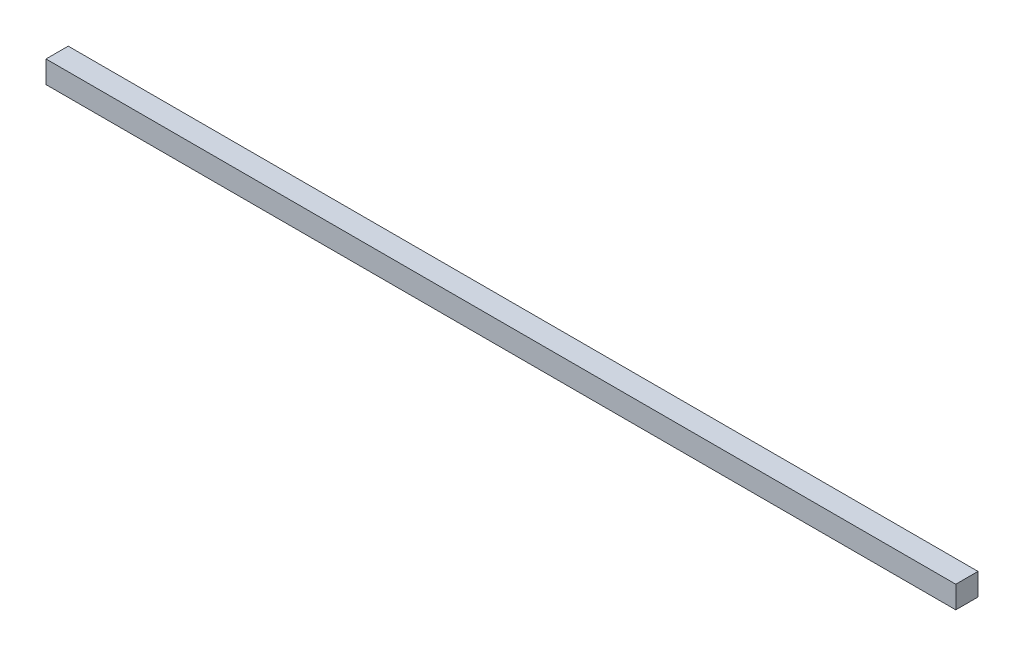
SolidWorks part; units mm, degrees
ref_plane "Front Plane" through (0, 0, 0) normal (0, 0, 1) x (1, 0, 0)
ref_plane "Top Plane" through (0, 0, 0) normal (0, 1, 0) x (1, 0, 0)
ref_plane "Right Plane" through (0, 0, 0) normal (1, 0, 0) x (0, 0, -1)
sketch "Sketch1" plane through (0, 0, 0) normal (1, 0, 0) x (0, 0, -1)
  line L1 (-1.5875, -1.5875) -> (1.5875, -1.5875) construction
  line L2 (-1.5875, -1.5875) -> (-1.5875, 1.5875) construction
  line L3 (-1.5875, 1.5875) -> (1.5875, 1.5875) construction
  line L4 (1.5875, -1.5875) -> (1.5875, 1.5875) construction
  line L5 (-1.5875, -1.5875) -> (1.5875, 1.5875) construction
  line L6 (-1.5875, 1.5875) -> (1.5875, -1.5875) construction
  point P0 (0, 0)
  dimension "Width" = 3.175
  dimension "Thickness" = 3.175
sketch "Sketch2" plane through (0, 0, 0) normal (0, 0, 1) x (1, 0, 0)
  line L0 (-65, 0) -> (65, 0) construction
  point P4 (0, 0)
  dimension "Length" = 130
sketch "Sketch3" plane through (0, 0, 0) normal (1, 0, 0) x (0, 0, -1)
  line L0 (1.5875, -1.5875) -> (1.5875, 1.5875) construction
  line L1 (-1.5875, -1.5875) -> (1.5875, -1.5875) construction
  line L2 (-1.5875, -1.5875) -> (-1.5875, 1.5875) construction
  line L3 (-1.5875, 1.5875) -> (1.5875, 1.5875) construction
  line L4 (1.5875, -1.5875) -> (1.5875, 1.5875)
  line L5 (-1.5875, -1.5875) -> (1.5875, -1.5875)
  line L6 (-1.5875, -1.5875) -> (-1.5875, 1.5875)
  line L7 (-1.5875, 1.5875) -> (1.5875, 1.5875)
extrude "Boss-Extrude1" add sketch "Sketch3" along normal up to vertex (65 mm away) and the other way up to vertex (65 mm away) up to point (65, 0, 0) other way up to point (-65, 0, 0)
